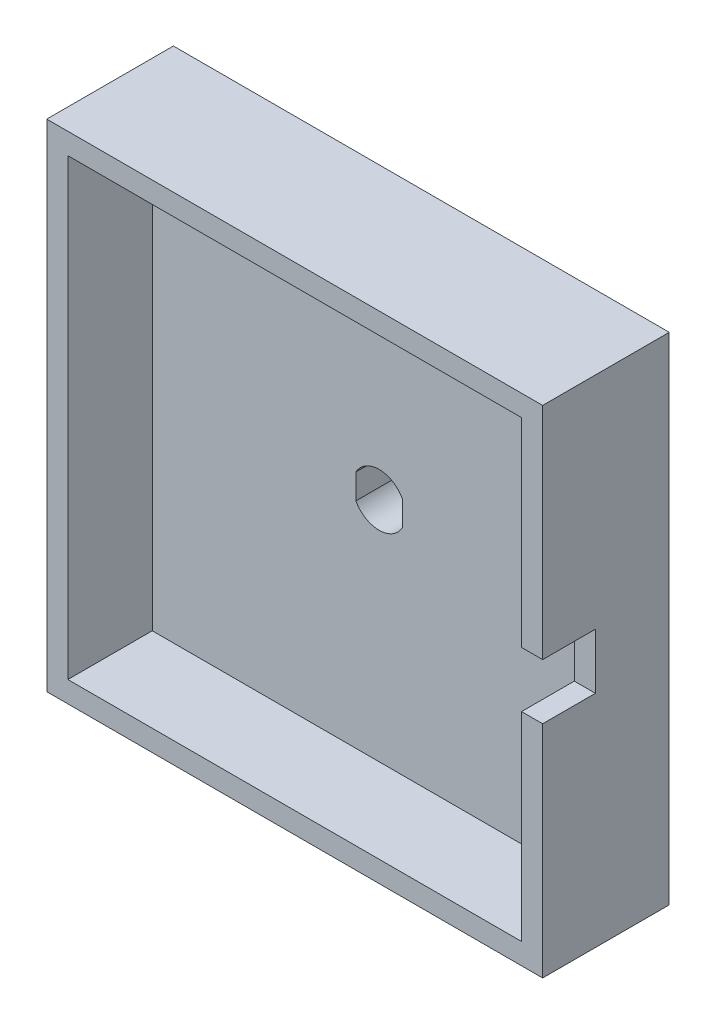
SolidWorks part; units mm, degrees
ref_plane "Front Plane" through (0, 0, 0) normal (0, 0, 1) x (1, 0, 0)
ref_plane "Top Plane" through (0, 0, 0) normal (0, 1, 0) x (1, 0, 0)
ref_plane "Right Plane" through (0, 0, 0) normal (1, 0, 0) x (0, 0, -1)
sketch "Sketch1" plane through (0, 0, 0) normal (0, 0, 1) x (1, 0, 0)
  line L1 (-23.5, 23.5) -> (23.5, 23.5)
  line L2 (-23.5, 23.5) -> (-23.5, -23.5)
  line L3 (-23.5, -23.5) -> (23.5, -23.5)
  line L4 (23.5, 23.5) -> (23.5, -23.5)
  line L5 (-23.5, 23.5) -> (23.5, -23.5) construction
  line L6 (-23.5, -23.5) -> (23.5, 23.5) construction
  point P0 (0, 0)
  dimension "D1" = 47
  dimension "D2" = 47
extrude "Boss-Extrude1" add sketch "Sketch1" along normal blind 4
sketch "Sketch2" plane through (0, 0, 4) normal (0, 0, 1) x (1, 0, 0)
  line L2 (0, 23.5) -> (0, -23.5) construction
  line L3 (23.5, 23.5) -> (-23.5, 23.5) construction
  line L4 (-23.5, -23.5) -> (23.5, -23.5) construction
  line L5 (-2.2, 1.1874) -> (-2.2, -1.1874)
  line L6 (2.2, -1.1874) -> (2.2, 1.1874)
  arc A1 (-2.2, -1.1874) -> (2.2, -1.1874) centre (0, 0) ccw
  arc A3 (-2.2, 1.1874) -> (-2.2, -1.1874) centre (0, 0) ccw construction
  arc A4 (2.2, 1.1874) -> (-2.2, 1.1874) centre (0, 0) ccw
  arc A5 (2.2, -1.1874) -> (2.2, 1.1874) centre (0, 0) ccw construction
  dimension "D1" = 2.2
  dimension "D2" = 5
  dimension "D3" = 2.2
extrude "Cut-Extrude1" cut sketch "Sketch2" against normal through all both and the other way through all
sketch "Sketch3" plane through (0, 0, 4) normal (0, 0, 1) x (1, 0, 0)
  line L0 (-23.5, 23.5) -> (-23.5, -23.5) construction
  line L1 (23.5, 23.5) -> (-23.5, 23.5) construction
  circle A0 centre (-17.5, 17.5) radius 2.5
  dimension "D2" = 5
  dimension "D1" = 6
  dimension "D3" = 6
extrude "Cut-Extrude2" cut sketch "Sketch3" against normal through all both and the other way through all
sketch "Sketch4" plane through (0, 0, 4) normal (0, 0, 1) x (1, 0, 0)
  line L1 (-23.5, 23.5) -> (23.5, 23.5)
  line L2 (-23.5, 23.5) -> (-23.5, -23.5)
  line L3 (-23.5, -23.5) -> (23.5, -23.5)
  line L4 (23.5, 23.5) -> (23.5, -23.5)
  line L5 (21.5, -21.5) -> (-21.5, -21.5)
  line L6 (21.5, -21.5) -> (21.5, 21.5)
  line L7 (21.5, 21.5) -> (-21.5, 21.5)
  line L8 (-21.5, -21.5) -> (-21.5, 21.5)
  line L9 (21.5, -21.5) -> (-21.5, 21.5) construction
  line L10 (21.5, 21.5) -> (-21.5, -21.5) construction
  point P6 (0, 0)
  dimension "D1" = 2
  dimension "D2" = 2
extrude "Boss-Extrude2" add sketch "Sketch4" along normal blind 8
sketch "Sketch5" plane through (0, 0, 12) normal (0, 0, 1) x (1, 0, 0)
  line L0 (21.5, 0) -> (23.5, 0) construction
  line L1 (21.5, -21.5) -> (21.5, 21.5) construction
  line L2 (23.5, -23.5) -> (23.5, 23.5) construction
  line L4 (21.5, -2.6318) -> (23.5, -2.6318)
  line L5 (21.5, -2.6318) -> (21.5, 2.6318)
  line L6 (21.5, 2.6318) -> (23.5, 2.6318)
  line L7 (23.5, -2.6318) -> (23.5, 2.6318)
  line L8 (21.5, -2.6318) -> (23.5, 2.6318) construction
  line L9 (21.5, 2.6318) -> (23.5, -2.6318) construction
  point P6 (22.5, 0)
extrude "Cut-Extrude3" cut sketch "Sketch5" against normal blind 5
